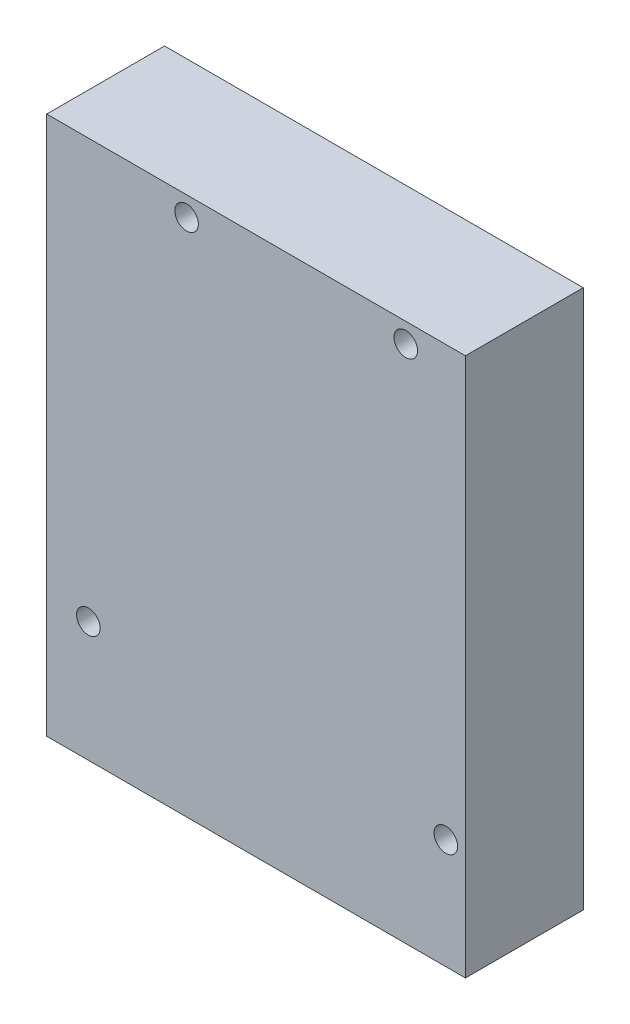
SolidWorks part; units mm, degrees
ref_plane "前视基准面" through (0, 0, 0) normal (0, 0, 1) x (1, 0, 0)
ref_plane "上视基准面" through (0, 0, 0) normal (0, 1, 0) x (1, 0, 0)
ref_plane "右视基准面" through (0, 0, 0) normal (1, 0, 0) x (0, 0, -1)
sketch "草图1" plane through (0, 0, 0) normal (0, 0, 1) x (1, 0, 0)
  line L1 (-37.7908, 53.4481) -> (15.5092, 53.4481)
  line L2 (-37.7908, 53.4481) -> (-37.7908, -15.1519)
  line L3 (-37.7908, -15.1519) -> (15.5092, -15.1519)
  line L4 (15.5092, 53.4481) -> (15.5092, -15.1519)
  circle A0 centre (-19.9908, 50.9481) radius 1.5
  circle A1 centre (7.9092, 50.9481) radius 1.5
  circle A2 centre (-32.4908, 0.1481) radius 1.5
  circle A3 centre (13.0092, -1.1519) radius 1.5
  point P14 (33.809, 38.2268)
  point P15 (35.0061, 27.9652)
  dimension "D1" = 3
  dimension "D2" = 27.9
  dimension "D3" = 12.5
  dimension "D4" = 50.8
  dimension "D5" = 1.3
  dimension "D6" = 5.1
  dimension "D7" = 68.6
  dimension "D8" = 53.3
  dimension "D9" = 14
  dimension "D10" = 2.5
extrude "凸台-拉伸1" add sketch "草图1" along normal blind 15
